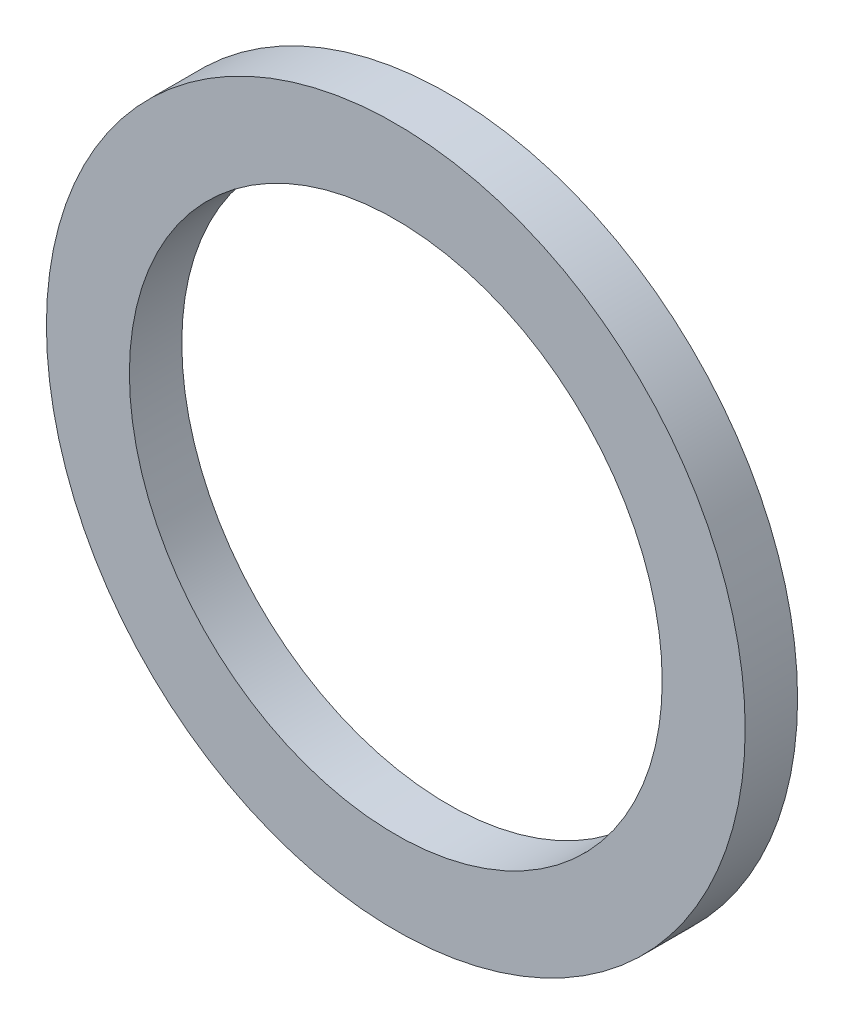
SolidWorks part; units mm, degrees
material "AISI 4340 Steel, normalized"
ref_plane "Front Plane" through (0, 0, 0) normal (0, 0, 1) x (1, 0, 0)
ref_plane "Top Plane" through (0, 0, 0) normal (0, 1, 0) x (1, 0, 0)
ref_plane "Right Plane" through (0, 0, 0) normal (1, 0, 0) x (0, 0, -1)
sketch "Sketch1" plane through (0, 0, 0) normal (0, 0, 1) x (1, 0, 0)
  circle A0 centre (0, 0) radius 2
  circle A1 centre (0, 0) radius 1.525
extrude "Inner_Race_Spacer_H0p3" add sketch "Sketch1" along normal blind 0.3 from offset 1.5
